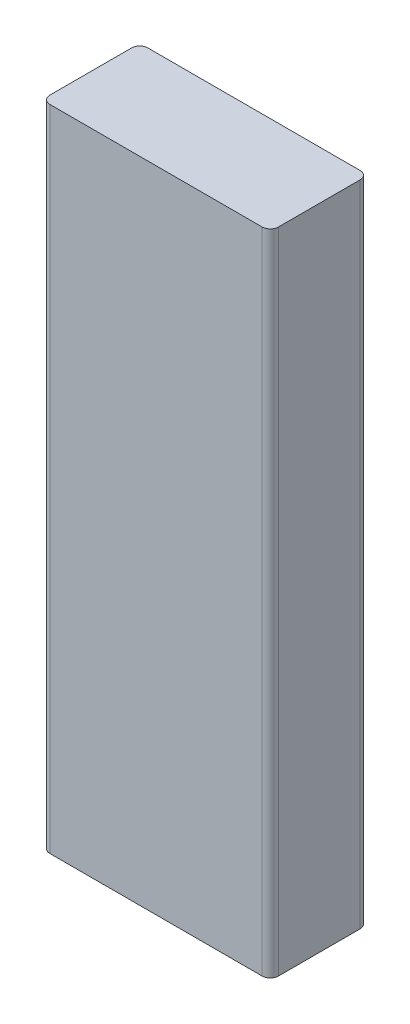
SolidWorks part; units mm, degrees
material "Pine"
ref_plane "Front Plane" through (0, 0, 0) normal (0, 0, 1) x (1, 0, 0)
ref_plane "Top Plane" through (0, 0, 0) normal (0, 1, 0) x (1, 0, 0)
ref_plane "Right Plane" through (0, 0, 0) normal (1, 0, 0) x (0, 0, -1)
sketch "Sketch1" plane through (0, 0, 0) normal (0, 1, 0) x (1, 0, 0)
  line L1 (-44.45, 19.05) -> (44.45, 19.05)
  line L2 (-44.45, 19.05) -> (-44.45, -19.05)
  line L3 (-44.45, -19.05) -> (44.45, -19.05)
  line L4 (44.45, 19.05) -> (44.45, -19.05)
  line L5 (-44.45, 19.05) -> (44.45, -19.05) construction
  line L6 (-44.45, -19.05) -> (44.45, 19.05) construction
  point P0 (0, 0)
  dimension "D1" = 38.1
  dimension "D2" = 88.9
extrude "Boss-Extrude1" add sketch "Sketch1" along normal blind 252.4125
fillet "Fillet1" radius 3.175 4 edges at (-44.45, 126.2062, 19.05) (-44.45, 126.2062, -19.05) (44.45, 126.2062, -19.05) (44.45, 126.2062, 19.05)
